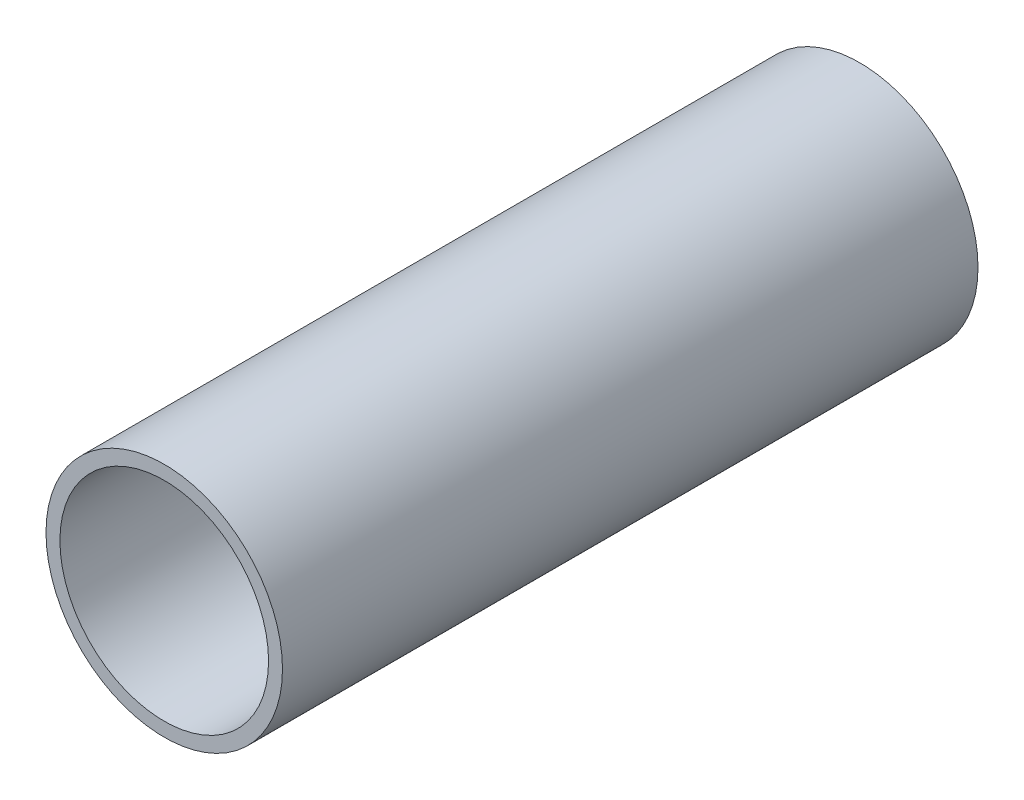
SolidWorks part; units mm, degrees
ref_plane "Front Plane" through (0, 0, 0) normal (0, 0, 1) x (1, 0, 0)
ref_plane "Top Plane" through (0, 0, 0) normal (0, 1, 0) x (1, 0, 0)
ref_plane "Right Plane" through (0, 0, 0) normal (1, 0, 0) x (0, 0, -1)
sketch "Sketch1" plane through (0, 0, 0) normal (0, 0, 1) x (1, 0, 0)
  circle A0 centre (0, 0) radius 30
  circle A1 centre (0, 0) radius 34
  dimension "D1" = 60
  dimension "D2" = 4
extrude "Boss-Extrude1" add sketch "Sketch1" along normal blind 200
